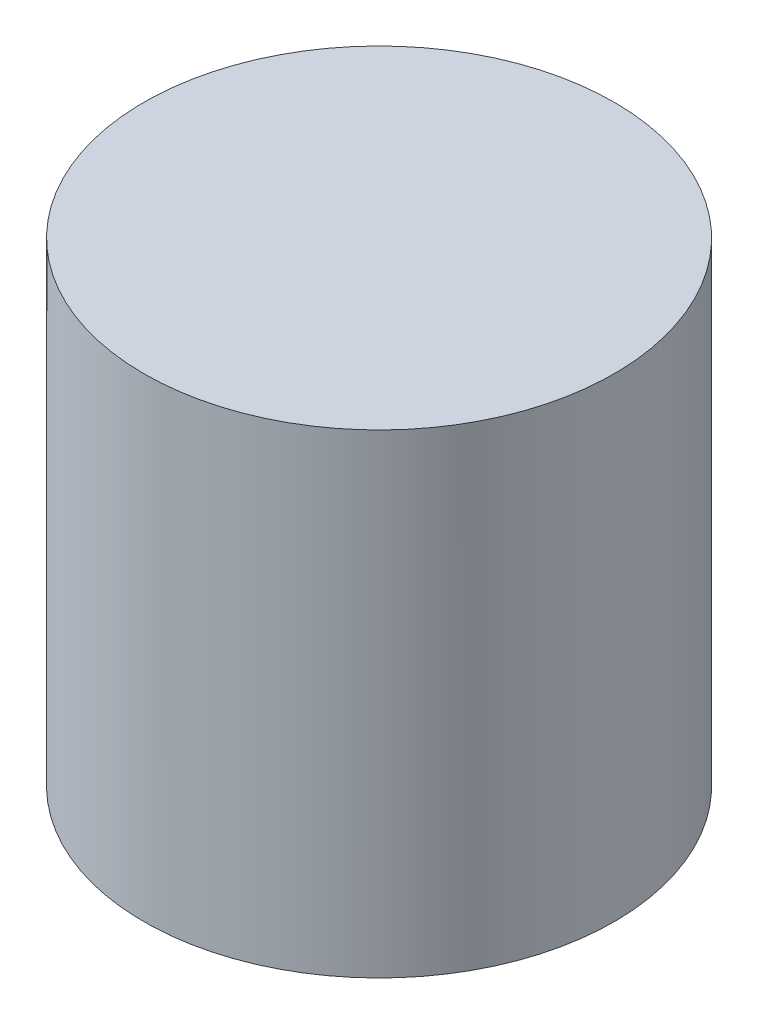
SolidWorks part; units mm, degrees
ref_plane "Front Plane" through (0, 0, 0) normal (0, 0, 1) x (1, 0, 0)
ref_plane "Top Plane" through (0, 0, 0) normal (0, 1, 0) x (1, 0, 0)
ref_plane "Right Plane" through (0, 0, 0) normal (1, 0, 0) x (0, 0, -1)
sketch "Sketch1" plane through (0, 0, 0) normal (0, 1, 0) x (1, 0, 0)
  line L0 (0, 0) -> (0, -25.9011) construction
  line L1 (0, 0) -> (32.9127, 0) construction
  line L2 (0, 0) -> (-28.4294, 0) construction
  line L3 (0, 0) -> (0, 27.1285) construction
  circle A0 centre (0, 0) radius 21.8 construction
  circle A1 centre (0, 0) radius 19.3 construction
  circle A2 centre (0, 0) radius 17.8 construction
  circle A3 centre (0, 0) radius 20.1 construction
  dimension "D1" = 43.6
  dimension "D2" = 2.5
  dimension "D3" = 4
  dimension "D4" = 1.7
sketch "Sketch2" plane through (0, 0, 0) normal (0, 1, 0) x (1, 0, 0)
  line L0 (0, 0) -> (-2.05, -24.2405) construction
  line L1 (2.0496, -24.2352) -> (0, 0) construction
  line L2 (-1.6264, -19.2313) -> (-1.5, -17.7367)
  line L3 (1.6264, -19.2313) -> (1.5, -17.7367)
  line L5 (0, 0) -> (-28.1862, 2.2238) construction
  line L6 (0, 0) -> (-30.0296, -2.3692) construction
  line L7 (0, 0) -> (-28.4941, -6.0552) construction
  line L8 (0, 0) -> (-31.2183, 6.6341) construction
  line L9 (-18.8784, 4.0118) -> (-17.4112, 3.7)
  line L10 (-20.0377, 1.5809) -> (-17.7449, 1.4)
  line L11 (-20.0377, -1.5809) -> (-17.7449, -1.4)
  line L12 (-18.8784, -4.0118) -> (-17.4112, -3.7)
  line L13 (0, 0) -> (-28.4294, 0) construction
  line L15 (0, -29.1663) -> (0, 29.1663) construction
  line L16 (18.8784, -4.0118) -> (17.4112, -3.7)
  line L17 (20.0377, -1.5809) -> (17.7449, -1.4)
  line L18 (20.0377, 1.5809) -> (17.7449, 1.4)
  line L19 (18.8784, 4.0118) -> (17.4112, 3.7)
  circle A0 centre (0, 0) radius 17.8 construction
  circle A1 centre (0, 0) radius 19.3 construction
  circle A2 centre (0, 0) radius 21.8 construction
  arc A3 (-1.5, -17.7367) -> (1.5, -17.7367) centre (0, 0) ccw
  arc A4 (18.8784, 4.0118) -> (-18.8784, 4.0118) centre (0, 0) ccw
  circle A5 centre (0, 0) radius 21.8
  arc A6 (18.8784, -4.0118) -> (1.6264, -19.2313) centre (0, 0) cw
  arc A7 (-17.7449, -1.4) -> (-17.4112, -3.7) centre (0, 0) ccw
  arc A9 (-18.8784, -4.0118) -> (-1.6264, -19.2313) centre (0, 0) ccw
  arc A10 (-20.0377, 1.5809) -> (-20.0377, -1.5809) centre (0, 0) ccw
  arc A11 (-17.4112, 3.7) -> (-17.7449, 1.4) centre (0, 0) ccw
  arc A12 (-1.5, -17.7367) -> (1.5, -17.7367) centre (0, 0) ccw
  arc A13 (17.7449, -1.4) -> (17.4112, -3.7) centre (0, 0) cw
  arc A14 (20.0377, 1.5809) -> (20.0377, -1.5809) centre (0, 0) cw
  arc A15 (17.4112, 3.7) -> (17.7449, 1.4) centre (0, 0) cw
  dimension "D1" = 4
  dimension "D2" = 2.5
  dimension "D3" = 3
  dimension "D5" = 2.8
  dimension "D6" = 1.4
  dimension "D7" = 2.3
  dimension "D8" = 2.3
extrude "Boss-Extrude1" add sketch "Sketch2" along normal blind 41 contours A15 L19 A4 L9 A11 L10 A10 L11 A7 L12 A9 L2 A3 L3 A6 L16 A13 L17 A14 L18 | A5
sketch "Sketch3" plane through (0, 0, 0) normal (0, -1, 0) x (1, 0, 0)
  line L0 (11, -18.8213) -> (11, -13.6107)
  line L1 (-11, -18.8213) -> (-11, -13.6107)
  line L2 (0, 0) -> (0, -27.1285) construction
  arc A0 (-11, -13.6107) -> (11, -13.6107) centre (0, 0) ccw
  circle A1 centre (0, 0) radius 21.8 construction
  arc A2 (-11, -18.8213) -> (11, -18.8213) centre (0, 0) ccw
  dimension "D1" = 4.3
  dimension "D2" = 22
  dimension "D3" = 11
extrude "Boss-Extrude2" add sketch "Sketch3" against normal up to surface (41 mm away) up to face at (0, 41, 3.2207)
ref_plane "Plane1" through (0, 0, -21.8) normal (0, 0, -1) x (-1, 0, 0)
sketch "Sketch4" plane through (0, 0, -21.8) normal (0, 0, -1) x (-1, 0, 0)
  line L0 (-9.5, 0) -> (9.5, 0)
  arc A0 (9.5, 0) -> (-9.5, 0) centre (0, 0) ccw
  dimension "D1" = 19
extrude "Cut-Extrude1" cut sketch "Sketch4" against normal up to next
ref_plane "Plane2" through (0, 0, -17.5) normal (0, 0, 1) x (1, 0, 0)
sketch "Sketch5" plane through (0, 0, -17.5) normal (0, 0, 1) x (1, 0, 0)
  line L0 (0, 9.5) -> (-7.7049, 9.5) construction
  line L1 (0, -22.55) -> (0, 22.55) construction
  line L4 (7, 20.3) -> (7, 29.3)
  line L5 (7, 29.3) -> (-7, 29.3)
  line L6 (-7, 20.3) -> (-7, 29.3)
  arc A0 (9.5, 0) -> (-9.5, 0) centre (0, 0) ccw construction
  arc A1 (-7, 20.3) -> (7, 20.3) centre (0, 20.3) ccw
  dimension "D1" = 14
  dimension "D2" = 10.8
  dimension "D3" = 14
  dimension "D4" = 9
extrude "Cut-Extrude2" cut sketch "Sketch5" against normal blind 2 and the other way up to next contours A1 L4 L5 L6
sketch "Sketch6" plane through (0, 41, 0) normal (0, 1, 0) x (1, 0, 0)
  circle A0 centre (0, 0) radius 21.8 construction
  circle A1 centre (0, 0) radius 21.8
extrude "Boss-Extrude3" add sketch "Sketch6" along normal blind 3
